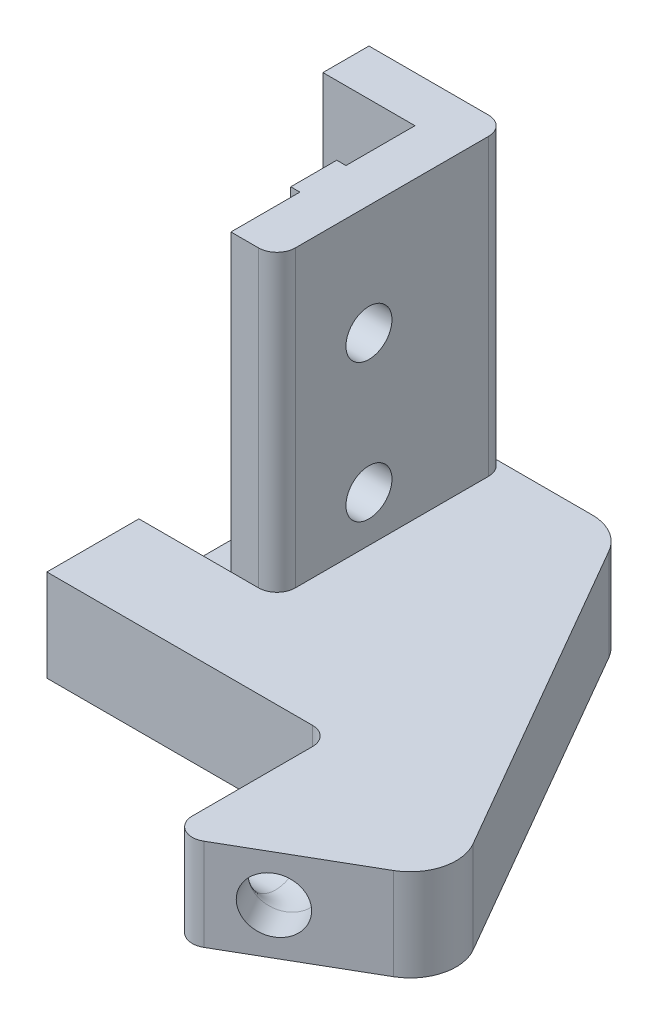
SolidWorks part; units mm, degrees
material "Custom Plastic"
ref_plane "Front Plane" through (0, 0, 0) normal (0, 0, 1) x (1, 0, 0)
ref_plane "Top Plane" through (0, 0, 0) normal (0, 1, 0) x (1, 0, 0)
ref_plane "Right Plane" through (0, 0, 0) normal (1, 0, 0) x (0, 0, -1)
sketch "Sketch1" plane through (0, 0, 0) normal (0, 1, 0) x (1, 0, 0)
  line L0 (-28.8675, 50) -> (-28.8675, 70) construction
  line L1 (-28.8675, 50) -> (-57.735, 0) construction
  line L2 (-57.735, 0) -> (-28.8675, -50) construction
  line L3 (-28.8675, -50) -> (28.8675, -50) construction
  line L4 (28.8675, -50) -> (57.735, 0) construction
  line L5 (57.735, 0) -> (28.8675, 50) construction
  line L6 (28.8675, 50) -> (-28.8675, 50) construction
  line L7 (-28.8675, 70) -> (28.8675, 70) construction
  line L8 (28.8675, 70) -> (28.8675, 50) construction
  line L9 (28.8675, 50) -> (46.188, 60) construction
  line L10 (46.188, 60) -> (75.0555, 10) construction
  line L11 (75.0555, 10) -> (57.735, 0) construction
  line L12 (57.735, 0) -> (75.0555, -10) construction
  line L13 (75.0555, -10) -> (46.188, -60) construction
  line L14 (46.188, -60) -> (28.8675, -50) construction
  line L15 (28.8675, -50) -> (28.8675, -70) construction
  line L16 (28.8675, -70) -> (-28.8675, -70) construction
  line L17 (-28.8675, -70) -> (-28.8675, -50) construction
  line L18 (-28.8675, -50) -> (-46.188, -60) construction
  line L19 (-46.188, -60) -> (-75.0555, -10) construction
  line L20 (-75.0555, -10) -> (-57.735, 0) construction
  line L21 (-57.735, 0) -> (-75.0555, 10) construction
  line L22 (-75.0555, 10) -> (-46.188, 60) construction
  line L23 (-46.188, 60) -> (-28.8675, 50) construction
  line L24 (-77.7876, 9.2679) -> (-46.9201, 62.7321)
  line L25 (-46.9201, 62.7321) -> (-30.8675, 53.4641)
  line L26 (-30.8675, 53.4641) -> (-30.8675, 72)
  line L27 (-30.8675, 72) -> (30.8675, 72)
  line L28 (30.8675, 72) -> (30.8675, 53.4641)
  line L29 (30.8675, 53.4641) -> (46.9201, 62.7321)
  line L30 (46.9201, 62.7321) -> (77.7876, 9.2679)
  line L31 (77.7876, 9.2679) -> (61.735, 0)
  line L32 (61.735, 0) -> (77.7876, -9.2679)
  line L33 (77.7876, -9.2679) -> (46.9201, -62.7321)
  line L34 (46.9201, -62.7321) -> (30.8675, -53.4641)
  line L35 (30.8675, -53.4641) -> (30.8675, -72)
  line L36 (30.8675, -72) -> (-30.8675, -72)
  line L37 (-30.8675, -72) -> (-30.8675, -53.4641)
  line L38 (-30.8675, -53.4641) -> (-46.9201, -62.7321)
  line L39 (-46.9201, -62.7321) -> (-77.7876, -9.2679)
  line L40 (-77.7876, -9.2679) -> (-61.735, 0)
  line L41 (-61.735, 0) -> (-77.7876, 9.2679)
  line L42 (76.0141, -32.3397) -> (66.0141, -49.6603)
  line L43 (-10, 82) -> (10, 82)
  line L44 (-10, 82) -> (-10, 102)
  line L45 (-10, 102) -> (10, 102)
  line L46 (10, 82) -> (10, 102)
  line L55 (76.0141, -32.3397) -> (93.3346, -42.3397)
  line L56 (93.3346, -42.3397) -> (83.3346, -59.6603)
  line L57 (66.0141, -49.6603) -> (83.3346, -59.6603)
  line L58 (-66.0141, -49.6603) -> (-76.0141, -32.3397)
  line L59 (-66.0141, -49.6603) -> (-83.3346, -59.6603)
  line L60 (-83.3346, -59.6603) -> (-93.3346, -42.3397)
  line L61 (-76.0141, -32.3397) -> (-93.3346, -42.3397)
  line L62 (-27.1355, 107) -> (27.1355, 107)
  line L63 (27.1355, 107) -> (106.2324, -30)
  line L64 (106.2324, -30) -> (79.097, -77)
  line L65 (79.097, -77) -> (-79.097, -77)
  line L66 (-79.097, -77) -> (-106.2324, -30)
  line L67 (-106.2324, -30) -> (-27.1355, 107)
  line L68 (-46.9201, 62.7321) -> (-51.2502, 65.2321)
  line L69 (46.9201, 62.7321) -> (51.2502, 65.2321)
  circle A0 centre (0, 0) radius 50 construction
  circle A2 centre (0, 0) radius 82 construction
  point P1 (0, 50)
  point P49 (0, 82)
  point P51 (-71.0141, -41)
  point P60 (71.0141, -41)
  point P67 (0, 102)
  dimension "D1" = 100
  dimension "D2" = 10
  dimension "D3" = 20
  dimension "D6" = 20
  dimension "D7" = 20
  dimension "D10" = 5
  dimension "D11" = 5
  dimension "D12" = 5
  dimension "D13" = 5
  dimension "D14" = 5
  dimension "D15" = 5
  dimension "D5" = 2
  dimension "D4" = 6
  dimension "D9" = 3
extrude "Boss-Extrude1" add sketch "Sketch1" along normal blind 10 contours L29 L69 L63 L62 L67 L68 L25 L26 L27 L28 L46 L43 L44 L45
ref_plane "Plane2" through (0, 5, 0) normal (0, 1, 0) x (1, 0, 0)
sketch "Sketch2" plane through (-30.8675, 0, 0) normal (1, 0, 0) x (0, 0, -1)
  line L0 (53.4641, 10) -> (53.4641, 0) construction
  line L2 (72, 10) -> (72, 0) construction
  circle A1 centre (62.5, 5) radius 3
  point P5 (53.4641, 5)
  dimension "D1" = 9.5
  dimension "D2" = 6
sketch "Sketch3" plane through (0, 5, 0) normal (0, 1, 0) x (1, 0, 0)
  line L0 (-30.8675, 62.5) -> (-34.3523, 62.5)
  line L1 (-30.8675, 59.5) -> (-30.8675, 65.5) construction
  line L2 (-36.9504, 61) -> (-38.6928, 57.9821)
  line L3 (-30.8675, 53.4641) -> (-51.2502, 65.2321) construction
  arc A0 (-34.3523, 62.5) -> (-36.9504, 61) centre (-34.3523, 59.5) ccw
  dimension "D1" = 3
sweep "Cut-Sweep1" cut profiles "Sketch2" path "Sketch3"
mirror "Mirror3" about plane through (0, 0, 0) normal (1, 0, 0) of "Cut-Sweep1"
sketch "Sketch4" plane through (0, 0, 0) normal (1, 0, 0) x (0, 0, -1)
  line L0 (65.2321, 0) -> (107, 0) construction
  line L1 (107, 0) -> (107, 10) construction
  line L2 (107, 10) -> (65.2321, 10) construction
  line L3 (53.4641, 0) -> (65.2321, 0) construction
  line L4 (65.2321, 10) -> (53.4641, 10) construction
  line L5 (53.4641, 10) -> (53.4641, 0) construction
  line L6 (65.2321, 0) -> (107, 0)
  line L7 (107, 0) -> (107, 10)
  line L8 (107, 10) -> (65.2321, 10)
  line L9 (53.4641, 0) -> (65.2321, 0)
  line L10 (65.2321, 10) -> (53.4641, 10)
  line L11 (53.4641, 10) -> (53.4641, 0)
extrude "Cut-Extrude1" cut sketch "Sketch4" against normal through all
sketch "Sketch5" plane through (0, 10, 0) normal (0, 1, 0) x (1, 0, 0)
  line L0 (10, 82) -> (10, 102)
  line L6 (10, 102) -> (0, 102)
  line L7 (0, 102) -> (0, 107)
  line L8 (0, 107) -> (15, 107)
  line L9 (0, 107) -> (27.1355, 107) construction
  line L10 (15, 107) -> (15, 82)
  line L17 (10, 82) -> (15, 82)
  point P5 (10, 114.704)
  dimension "D3" = 5
extrude "Boss-Extrude2" add sketch "Sketch5" along normal blind 32 and the other way up to surface (10 mm away) other way up to face at (16.0121, 0, -84.4696)
sketch "Sketch7" plane through (10, 0, 0) normal (1, 0, 0) x (0, 0, -1)
  line L1 (82, 10) -> (107, 10) construction
  line L3 (102, 42) -> (82, 42) construction
  circle A0 centre (92, 15) radius 2.5
  circle A1 centre (92, 30) radius 2.5
  point P4 (0, 0)
  point P5 (0, 0)
  point P6 (94.3992, 15)
  point P10 (0, 0)
  point P12 (92, 42)
  dimension "D1" = 5
  dimension "D2" = 5
  dimension "D3" = 5
  dimension "D4" = 15
extrude "Cut-Extrude3" cut sketch "Sketch7" along normal blind 20
sketch "Sketch8" plane through (0, 0, 0) normal (0, -1, 0) x (1, 0, 0)
  line L1 (0, -102) -> (10, -102)
  line L2 (0, -102) -> (0, -82)
  line L3 (0, -82) -> (10, -82)
  line L4 (10, -102) -> (10, -82)
extrude "Boss-Extrude4" add sketch "Sketch8" against normal blind 3
sketch "Sketch9" plane through (10, 0, 0) normal (-1, 0, 0) x (0, 0, 1)
  line L0 (-94.5, 3) -> (-94.5, 12.5505)
  line L1 (-102, 3) -> (-82, 3) construction
  line L3 (-89.5, 3) -> (-89.5, 12.5505)
  line L4 (-89.5, 42) -> (-94.5, 42)
  line L5 (-94.5, 3) -> (-89.5, 3)
  line L6 (-82, 3) -> (-102, 3) construction
  line L7 (-94.5, 17.4495) -> (-94.5, 27.5505)
  line L8 (-89.5, 17.4495) -> (-89.5, 27.5505)
  line L9 (-89.5, 32.4495) -> (-89.5, 42)
  line L10 (-94.5, 32.4495) -> (-94.5, 42)
  line L11 (-102, 42) -> (-82, 42) construction
  circle A2 centre (-92, 15) radius 3.5
  arc A3 (-94.5, 12.5505) -> (-89.5, 12.5505) centre (-92, 15) ccw
  arc A4 (-89.5, 17.4495) -> (-94.5, 17.4495) centre (-92, 15) ccw
  circle A5 centre (-92, 30) radius 3.5
  arc A6 (-89.5, 32.4495) -> (-94.5, 32.4495) centre (-92, 30) ccw
  arc A7 (-94.5, 27.5505) -> (-89.5, 27.5505) centre (-92, 30) ccw
  point P14 (-106.1545, 3)
  point P17 (-92, 3)
  point P18 (-92, 3)
  dimension "D3" = 5
  dimension "D1" = 1
  dimension "D2" = 1
extrude "Boss-Extrude5" add sketch "Sketch9" along normal blind 1
fillet "Fillet1" radius 0.25 8 edges at (9.5, 27.5505, -89.5) (9.5, 27.5505, -94.5) (9.5, 32.4495, -94.5) (9.5, 32.4495, -89.5) (9.5, 17.4495, -94.5) (9.5, 17.4495, -89.5) (9.5, 12.5505, -89.5) (9.5, 12.5505, -94.5)
fillet "Fillet3" radius 2 4 edges at (30.8675, 5, -72) (15, 26, -82) (15, 26, -107) (30.8675, 5, -53.4641)
fillet "Fillet4" radius 5 2 edges at (27.1355, 5, -107) (51.2502, 5, -65.2321)
